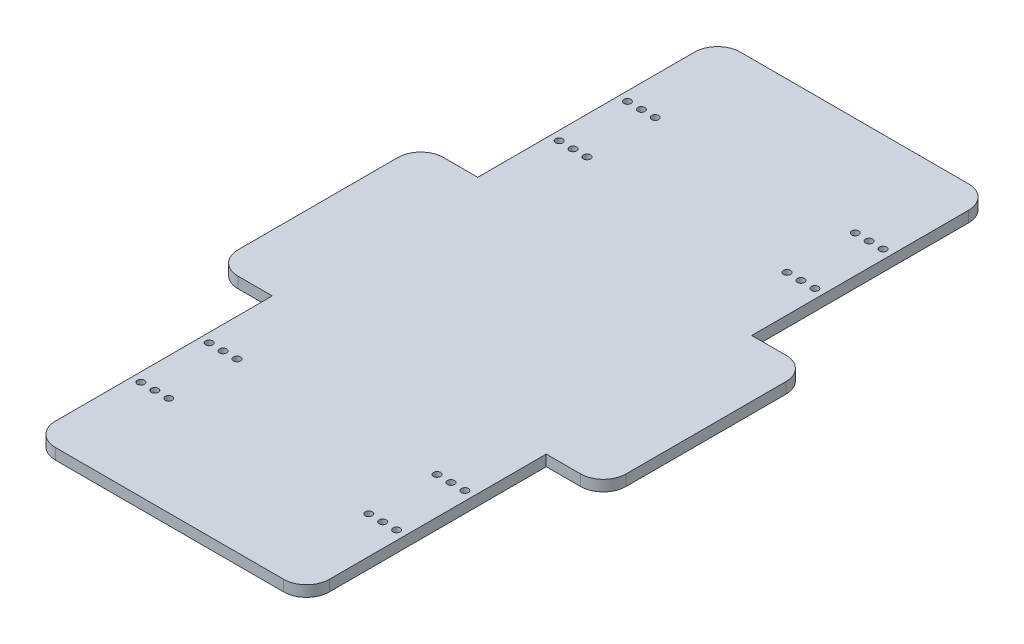
SolidWorks part; units mm, degrees
material "Acrylic (Medium-high impact)"
ref_plane "Front Plane" through (0, 0, 0) normal (0, 0, 1) x (1, 0, 0)
ref_plane "Top Plane" through (0, 0, 0) normal (0, 1, 0) x (1, 0, 0)
ref_plane "Right Plane" through (0, 0, 0) normal (1, 0, 0) x (0, 0, -1)
sketch "Sketch1" plane through (0, 0, 0) normal (0, 1, 0) x (1, 0, 0)
  line L0 (-154.5855, 0) -> (184.0933, 0) construction
  line L1 (-85, 150) -> (85, 150)
  line L2 (-85, 150) -> (-85, -150)
  line L3 (-85, -150) -> (85, -150)
  line L4 (85, 150) -> (85, -150)
  line L5 (-85, 150) -> (85, -150) construction
  line L6 (-85, -150) -> (85, 150) construction
  line L7 (-85, 150) -> (-60, 150)
  line L8 (-85, 150) -> (-85, 45)
  line L9 (-85, 45) -> (-60, 45)
  line L10 (-60, 150) -> (-60, 45)
  line L11 (0, -177.7073) -> (0, 159.6503) construction
  line L12 (-85, -45) -> (-60, -45)
  line L13 (-60, -150) -> (-60, -45)
  line L14 (-85, -150) -> (-60, -150)
  line L15 (-85, -150) -> (-85, -45)
  line L16 (85, -150) -> (60, -150)
  line L17 (60, -150) -> (60, -45)
  line L18 (85, -45) -> (60, -45)
  line L19 (85, -150) -> (85, -45)
  line L20 (85, 45) -> (60, 45)
  line L21 (60, 150) -> (60, 45)
  line L22 (85, 150) -> (60, 150)
  line L23 (85, 150) -> (85, 45)
  point P0 (0, 0)
  dimension "D1" = 170
  dimension "D2" = 300
  dimension "D3" = 25
  dimension "D4" = 105
extrude "Boss-Extrude1" add sketch "Sketch1" along normal blind 4.8 contours L21 L1 L10 L9 L2 L12 L13 L3 L17 L18 L4 L20
sketch "Sketch2" plane through (0, 4.8, 0) normal (0, 1, 0) x (1, 0, 0)
  circle A0 centre (56.0035, -76.643) radius 1.55
  circle A1 centre (49.9035, -76.643) radius 1.55
  circle A2 centre (56.0035, -106.543) radius 1.55
  circle A3 centre (49.9035, -106.543) radius 1.55
  circle A4 centre (43.8035, -76.643) radius 1.55
  circle A5 centre (43.8035, -106.543) radius 1.55
  point P10 (0, 0)
  dimension "D1" = 3.1
  dimension "D2" = 6.1
  dimension "D3" = 29.9
  dimension "D4" = 6.1
  dimension "D5" = 6.1
extrude "Cut-Extrude1" cut sketch "Sketch2" against normal blind 4.8
mirror "Mirror1" about plane through (0, 0, 0) normal (1, 0, 0) of "Cut-Extrude1"
mirror "Mirror2" about plane through (0, 0, 0) normal (0, 0, 1) of "Mirror1", "Cut-Extrude1"
fillet "Fillet1" radius 10 8 edges at (-60, 2.4, -150) (-85, 2.4, -45) (-85, 2.4, 45) (-60, 2.4, 150) (60, 2.4, -150) (85, 2.4, -45) (85, 2.4, 45) (60, 2.4, 150)
